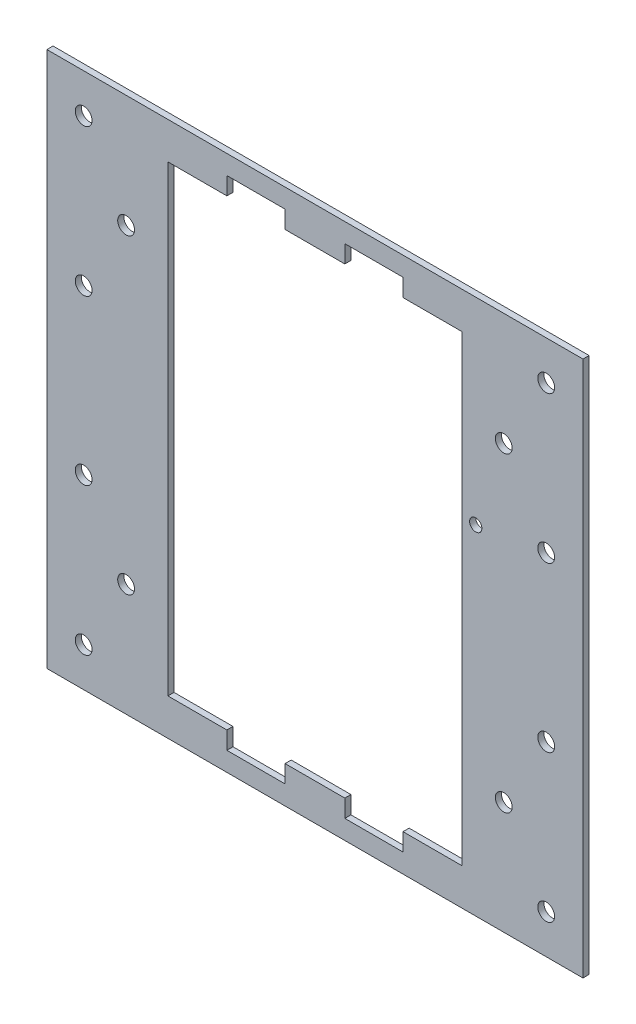
SolidWorks part; units mm, degrees
ref_plane "前视基准面" through (0, 0, 0) normal (0, 0, 1) x (1, 0, 0)
ref_plane "上视基准面" through (0, 0, 0) normal (0, 1, 0) x (1, 0, 0)
ref_plane "右视基准面" through (0, 0, 0) normal (1, 0, 0) x (0, 0, -1)
other "Configuration Table"
sketch "草图1" plane through (0, 0, 0) normal (0, 0, 1) x (1, 0, 0)
  line L0 (0, 0) -> (700, 0)
  line L1 (700, 0) -> (700, 700)
  line L2 (700, 700) -> (0, 700)
  line L3 (0, 700) -> (0, 0)
  dimension "width" = 700
  dimension "height" = 700
extrude "Connection_plate" add sketch "草图1" along normal blind 8
sketch "草图2" plane through (0, 0, 8) normal (0, 0, 1) x (1, 0, 0)
  line L0 (235, 25) -> (311, 25)
  line L1 (311, 25) -> (311, 325)
  line L2 (311, 325) -> (235, 325)
  line L3 (235, 325) -> (235, 25)
  dimension "x0" = 235
  dimension "x1" = 311
  dimension "y0" = 25
  dimension "y2" = 325
extrude "Access_window" cut sketch "草图2" against normal through all
sketch "草图3" plane through (0, 0, 8) normal (0, 0, 1) x (1, 0, 0)
  line L0 (235, 375) -> (311, 375)
  line L1 (311, 375) -> (311, 675)
  line L2 (311, 675) -> (235, 675)
  line L3 (235, 675) -> (235, 375)
  dimension "x0" = 235
  dimension "x1" = 311
  dimension "y0" = 375
  dimension "y2" = 675
extrude "切除-拉伸2" cut sketch "草图3" against normal through all
sketch "草图4" plane through (0, 0, 8) normal (0, 0, 1) x (1, 0, 0)
  line L0 (389, 25) -> (465, 25)
  line L1 (465, 25) -> (465, 325)
  line L2 (465, 325) -> (389, 325)
  line L3 (389, 325) -> (389, 25)
  dimension "x0" = 389
  dimension "x1" = 465
  dimension "y0" = 25
  dimension "y2" = 325
extrude "切除-拉伸3" cut sketch "草图4" against normal through all
sketch "草图5" plane through (0, 0, 8) normal (0, 0, 1) x (1, 0, 0)
  line L0 (389, 375) -> (465, 375)
  line L1 (465, 375) -> (465, 675)
  line L2 (465, 675) -> (389, 675)
  line L3 (389, 675) -> (389, 375)
  dimension "x0" = 389
  dimension "x1" = 465
  dimension "y0" = 375
  dimension "y2" = 675
extrude "切除-拉伸4" cut sketch "草图5" against normal through all
sketch "草图6" plane through (0, 0, 8) normal (0, 0, 1) x (1, 0, 0)
  circle A0 centre (48, 51) radius 11
  dimension "diameter" = 22
  dimension "x" = 48
  dimension "y" = 51
extrude "Shaft_clearance" cut sketch "草图6" against normal through all
sketch "草图7" plane through (0, 0, 8) normal (0, 0, 1) x (1, 0, 0)
  circle A0 centre (48, 243) radius 11
  dimension "diameter" = 22
  dimension "x" = 48
  dimension "y" = 243
extrude "切除-拉伸6" cut sketch "草图7" against normal through all
sketch "草图8" plane through (0, 0, 8) normal (0, 0, 1) x (1, 0, 0)
  circle A0 centre (48, 457) radius 11
  dimension "diameter" = 22
  dimension "x" = 48
  dimension "y" = 457
extrude "切除-拉伸7" cut sketch "草图8" against normal through all
sketch "草图9" plane through (0, 0, 8) normal (0, 0, 1) x (1, 0, 0)
  circle A0 centre (48, 649) radius 11
  dimension "diameter" = 22
  dimension "x" = 48
  dimension "y" = 649
extrude "切除-拉伸8" cut sketch "草图9" against normal through all
sketch "草图10" plane through (0, 0, 8) normal (0, 0, 1) x (1, 0, 0)
  circle A0 centre (103.43, 147) radius 11
  dimension "diameter" = 22
  dimension "x" = 103.43
  dimension "y" = 147
extrude "切除-拉伸9" cut sketch "草图10" against normal through all
sketch "草图11" plane through (0, 0, 8) normal (0, 0, 1) x (1, 0, 0)
  circle A0 centre (103.43, 553) radius 11
  dimension "diameter" = 22
  dimension "x" = 103.43
  dimension "y" = 553
extrude "切除-拉伸10" cut sketch "草图11" against normal through all
sketch "草图12" plane through (0, 0, 8) normal (0, 0, 1) x (1, 0, 0)
  circle A0 centre (652, 51) radius 11
  dimension "diameter" = 22
  dimension "x" = 652
  dimension "y" = 51
extrude "切除-拉伸11" cut sketch "草图12" against normal through all
sketch "草图13" plane through (0, 0, 8) normal (0, 0, 1) x (1, 0, 0)
  circle A0 centre (652, 243) radius 11
  dimension "diameter" = 22
  dimension "x" = 652
  dimension "y" = 243
extrude "切除-拉伸12" cut sketch "草图13" against normal through all
sketch "草图14" plane through (0, 0, 8) normal (0, 0, 1) x (1, 0, 0)
  circle A0 centre (652, 457) radius 11
  dimension "diameter" = 22
  dimension "x" = 652
  dimension "y" = 457
extrude "切除-拉伸13" cut sketch "草图14" against normal through all
sketch "草图15" plane through (0, 0, 8) normal (0, 0, 1) x (1, 0, 0)
  circle A0 centre (652, 649) radius 11
  dimension "diameter" = 22
  dimension "x" = 652
  dimension "y" = 649
extrude "切除-拉伸14" cut sketch "草图15" against normal through all
sketch "草图16" plane through (0, 0, 8) normal (0, 0, 1) x (1, 0, 0)
  circle A0 centre (596.57, 147) radius 11
  dimension "diameter" = 22
  dimension "x" = 596.57
  dimension "y" = 147
extrude "切除-拉伸15" cut sketch "草图16" against normal through all
sketch "草图17" plane through (0, 0, 8) normal (0, 0, 1) x (1, 0, 0)
  circle A0 centre (596.57, 553) radius 11
  dimension "diameter" = 22
  dimension "x" = 596.57
  dimension "y" = 553
extrude "切除-拉伸16" cut sketch "草图17" against normal through all
sketch "草图18" plane through (0, 0, 8) normal (0, 0, 1) x (1, 0, 0)
  line L0 (158, 48) -> (542, 48)
  line L1 (542, 48) -> (542, 652)
  line L2 (542, 652) -> (158, 652)
  line L3 (158, 652) -> (158, 48)
  dimension "x0" = 158
  dimension "x1" = 542
  dimension "y0" = 48
  dimension "y2" = 652
extrude "Float_installation_window" cut sketch "草图18" against normal through all
sketch "草图19" plane through (0, 0, 8) normal (0, 0, 1) x (1, 0, 0)
  circle A0 centre (560, 442.45) radius 8
  dimension "diameter" = 16
  dimension "x" = 560
  dimension "y" = 442.45
extrude "Comms_passage" cut sketch "草图19" against normal through all
